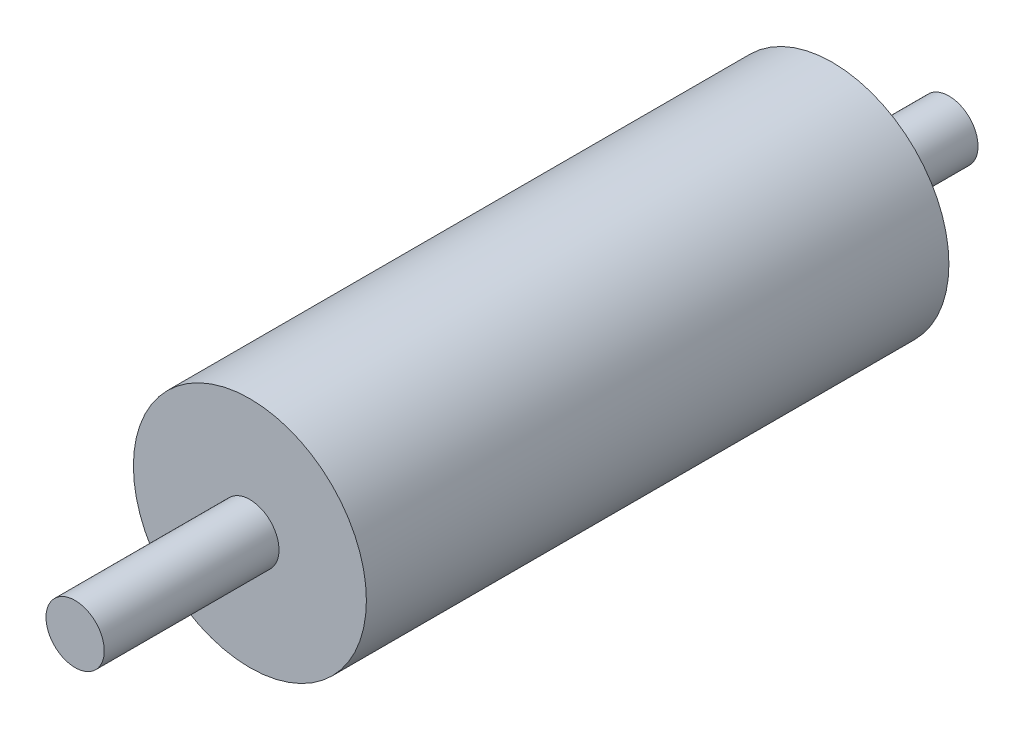
SolidWorks part; units mm, degrees
ref_plane "Front Plane" through (0, 0, 0) normal (0, 0, 1) x (1, 0, 0)
ref_plane "Top Plane" through (0, 0, 0) normal (0, 1, 0) x (1, 0, 0)
ref_plane "Right Plane" through (0, 0, 0) normal (1, 0, 0) x (0, 0, -1)
sketch "Sketch1" plane through (0, 0, 0) normal (0, 0, 1) x (1, 0, 0)
  circle A0 centre (0, 0) radius 20
  dimension "D1" = 40
extrude "Boss-Extrude1" add sketch "Sketch1" along normal blind 100
sketch "Sketch2" plane through (0, 0, 100) normal (0, 0, 1) x (1, 0, 0)
  circle A0 centre (0, 0) radius 5
  dimension "D1" = 10
extrude "Boss-Extrude2" add sketch "Sketch2" along normal blind 30
pattern_linear "LPattern1" count 2 spacing 130 along (0, 0, -1) of "Boss-Extrude2"
sketch "Sketch3" plane through (0, 0, -30) normal (0, 0, -1) x (-1, 0, 0)
  circle A0 centre (0, 0) radius 7.5
extrude "Cut-Extrude1" cut sketch "Sketch3" against normal blind 10
